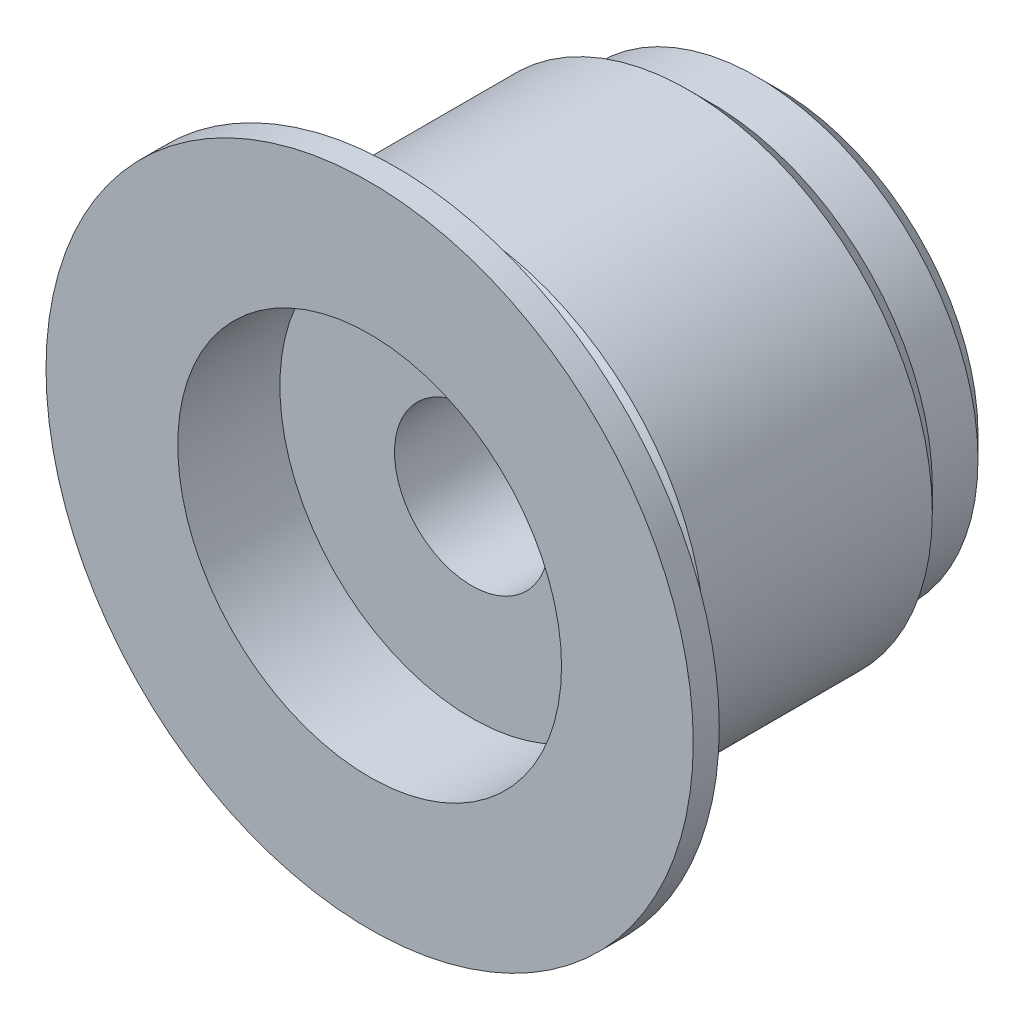
SolidWorks part; units mm, degrees
ref_plane "Front Plane" through (0, 0, 0) normal (0, 0, 1) x (1, 0, 0)
ref_plane "Top Plane" through (0, 0, 0) normal (0, 1, 0) x (1, 0, 0)
ref_plane "Right Plane" through (0, 0, 0) normal (1, 0, 0) x (0, 0, -1)
sketch "Sketch1" plane through (0, 0, 0) normal (0, 1, 0) x (1, 0, 0)
  line L1 (-12.6365, 0) -> (-12.6365, 1.016)
  line L3 (0, 16.002) -> (-9.525, 16.002) construction
  line L4 (-9.525, 16.002) -> (-9.525, 0) construction
  line L5 (-9.525, 12.446) -> (-9.525, 3.556)
  line L6 (-9.525, 12.446) -> (-8.627, 13.344)
  line L7 (-8.627, 13.344) -> (-8.627, 15.1277)
  line L8 (-8.627, 15.1277) -> (-7.7527, 16.002)
  line L9 (-7.7527, 16.002) -> (0, 16.002)
  line L10 (-9.525, 3.556) -> (-8.9618, 2.9928)
  line L11 (-8.9618, 2.9928) -> (-12.6365, 1.016)
  line L12 (0, 0) -> (-7.493, 0) construction
  line L13 (-7.493, 0) -> (-7.493, 3.9878)
  line L14 (0, 0) -> (0, 12.954) construction
  line L15 (0, 12.954) -> (-3.0162, 12.954) construction
  line L16 (-3.0162, 12.954) -> (-3.0162, 3.9878)
  line L17 (-3.0162, 3.9878) -> (-7.493, 3.9878)
  line L18 (-3.0162, 12.954) -> (0, 14.7663)
  line L19 (-12.6365, 0) -> (-7.493, 0)
  line L20 (0, 16.002) -> (0, 14.7663)
  point P10 (-9.525, 8.001)
  dimension "D1" = 12.6365
  dimension "D2" = 1.016
  dimension "D3" = 16.002
  dimension "D4" = 9.525
  dimension "D5" = 8.89
  dimension "D6" = 45
  dimension "D7" = 12.954
  dimension "D8" = 31
revolve "Revolve1" add sketch "Sketch1" angle 360 about L14
